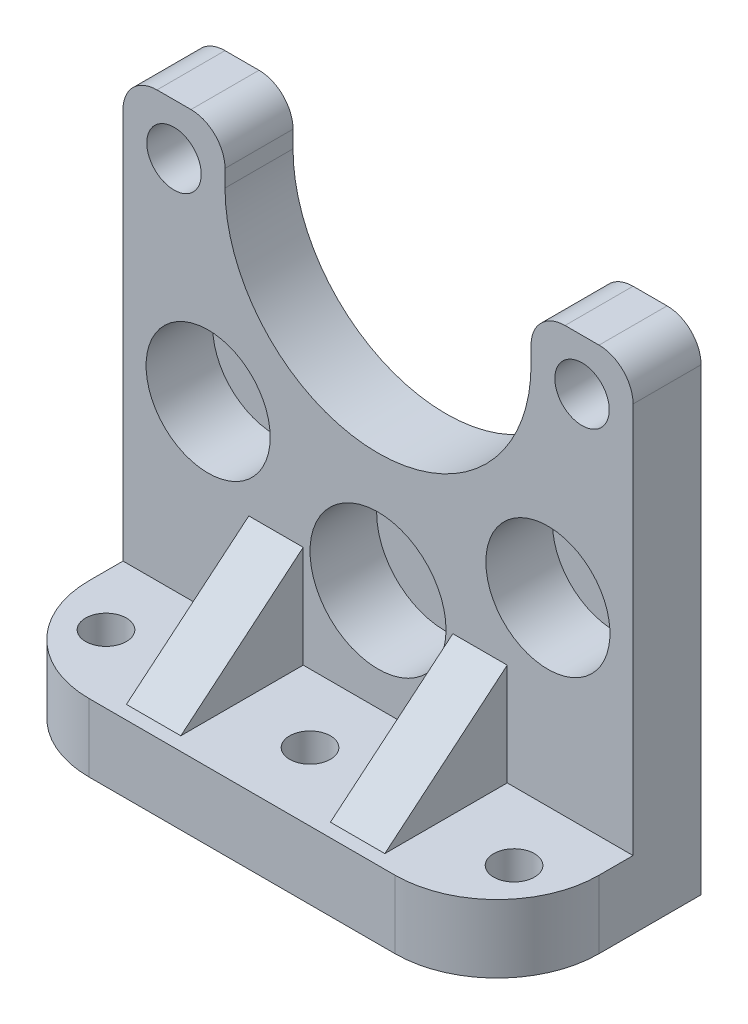
SolidWorks part; units mm, degrees
ref_plane "Front Plane" through (0, 0, 0) normal (0, 0, 1) x (1, 0, 0)
ref_plane "Top Plane" through (0, 0, 0) normal (0, 1, 0) x (1, 0, 0)
ref_plane "Right Plane" through (0, 0, 0) normal (1, 0, 0) x (0, 0, -1)
sketch "Sketch1" plane through (0, 0, 0) normal (0, 0, 1) x (1, 0, 0)
  line L1 (0, 0) -> (75, 0)
  line L2 (0, 0) -> (0, 72.5)
  line L3 (0, 72.5) -> (75, 72.5)
  line L4 (75, 0) -> (75, 72.5)
  dimension "D1" = 72.5
  dimension "D2" = 75
extrude "Boss-Extrude1" add sketch "Sketch1" along normal blind 10
sketch "Sketch2" plane through (0, 0, 10) normal (0, 0, 1) x (1, 0, 0)
  line L1 (37.5, 72.5) -> (37.5, 0) construction
  line L3 (75, 72.5) -> (0, 72.5) construction
  line L4 (0, 0) -> (75, 0) construction
  line L7 (60, 65) -> (60, 72.5)
  line L8 (60, 72.5) -> (15, 72.5)
  line L9 (15, 65) -> (15, 72.5)
  arc A0 (15, 65) -> (60, 65) centre (37.5, 65) ccw
  dimension "D1" = 65
  dimension "D2" = 22.5
extrude "Cut-Extrude1" cut sketch "Sketch2" against normal up to surface (10 mm away) up to face at (37.5, 36.25, 0)
sketch "Sketch3" plane through (0, 0, 10) normal (0, 0, 1) x (1, 0, 0)
  line L0 (75, 0) -> (75, 72.5) construction
  line L1 (0, 0) -> (75, 0)
  line L2 (0, 0) -> (0, 10)
  line L3 (0, 10) -> (75, 10)
  line L4 (75, 0) -> (75, 10)
  dimension "D1" = 10
extrude "feet" add sketch "Sketch3" along normal blind 20
sketch "Sketch4" plane through (0, 0, 0) normal (0, -1, 0) x (1, 0, 0)
  line L2 (37.5, 30) -> (37.5, 0) construction
  line L3 (0, 30) -> (75, 30) construction
  line L4 (0, 0) -> (75, 0) construction
  circle A0 centre (7.5, 20) radius 3
  circle A1 centre (67.5, 20) radius 3
  circle A2 centre (37.5, 20) radius 3
  dimension "D1" = 6
  dimension "D2" = 30
  dimension "D3" = 30
  dimension "D6" = 20
extrude "feet-hole" cut sketch "Sketch4" against normal up to surface (10 mm away) up to face at (46.875, 10, 25)
sketch "Sketch5" plane through (0, 0, 10) normal (0, 0, 1) x (1, 0, 0)
  line L0 (37.5, 42.5) -> (37.5, 65) construction
  line L1 (7.5, 72.5) -> (7.5, 49.9689) construction
  line L2 (15, 72.5) -> (0, 72.5) construction
  line L3 (-11.3931, 65) -> (60.2155, 65) construction
  line L5 (75, 10) -> (0, 10) construction
  arc A0 (15, 65) -> (60, 65) centre (37.5, 65) ccw construction
  circle A1 centre (7.5, 65) radius 4
  circle A2 centre (67.5, 65) radius 4
  circle A3 centre (37.5, 25) radius 10
  circle A4 centre (12.5192, 36.5793) radius 9.1247
  circle A5 centre (62.4808, 36.5793) radius 9.1247
  dimension "D1" = 20
  dimension "D3" = 15
sketch "Sketch6" plane through (0, 0, 10) normal (0, 0, 1) x (1, 0, 0)
  line L0 (75, 10) -> (0, 10) construction
  line L1 (18.5, 10) -> (26.5, 10)
  line L2 (18.5, 10) -> (18.5, 25)
  line L3 (18.5, 25) -> (26.5, 25)
  line L4 (26.5, 10) -> (26.5, 25)
  line L5 (37.5, 42.5) -> (37.5, 65) construction
  line L6 (37.5, 65) -> (37.5, -5.7532) construction
  line L7 (48.5, 10) -> (48.5, 25)
  line L8 (56.5, 25) -> (48.5, 25)
  line L9 (56.5, 10) -> (56.5, 25)
  line L10 (56.5, 10) -> (48.5, 10)
  dimension "D1" = 8
  dimension "D2" = 15
  dimension "D3" = 11
extrude "Boss-Extrude2" add sketch "Sketch6" along normal offset from surface (18 mm away) 2 up to face at (37.5, 5, 30)
sketch "Sketch7" plane through (18.5, 0, 0) normal (-1, 0, 0) x (0, 0, 1)
  line L0 (10, 25) -> (28, 10)
  line L1 (28, 10) -> (10, 10) construction
  line L2 (28, 10) -> (28, 25) construction
  line L3 (28, 10) -> (28, 25)
  line L4 (28, 25) -> (10, 25)
extrude "Cut-Extrude2" cut sketch "Sketch7" against normal through all
extrude "Cut-Extrude3" cut sketch "Sketch5" against normal offset from surface (9.8 mm away) 0.2 up to face at (37.5, 49.6875, 0)
fillet "Fillet1" radius 5 4 edges at (0, 72.5, 5) (15, 72.5, 5) (60, 72.5, 5) (75, 72.5, 5)
fillet "Fillet2" radius 15 2 edges at (0, 5, 30) (75, 5, 30)
